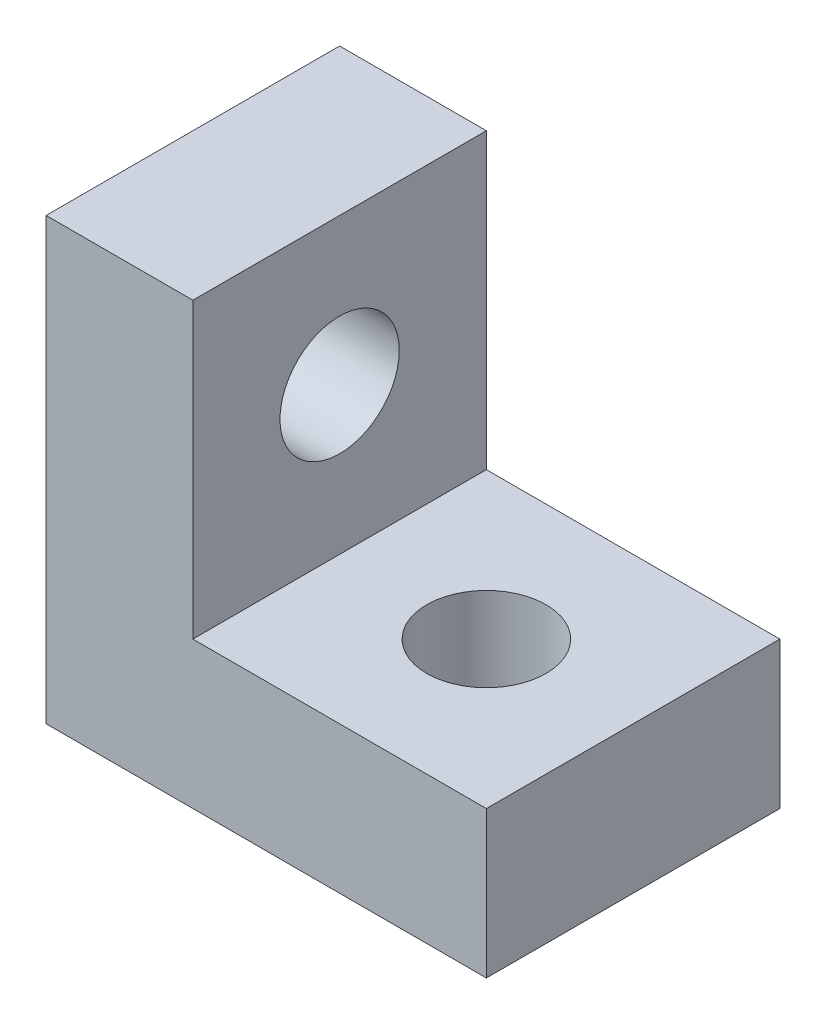
SolidWorks part; units mm, degrees
ref_plane "Front Plane" through (0, 0, 0) normal (0, 0, 1) x (1, 0, 0)
ref_plane "Top Plane" through (0, 0, 0) normal (0, 1, 0) x (1, 0, 0)
ref_plane "Right Plane" through (0, 0, 0) normal (1, 0, 0) x (0, 0, -1)
sketch "Sketch1" plane through (0, 0, 0) normal (0, 0, 1) x (1, 0, 0)
  line L1 (0, 0) -> (11.1626, 0)
  line L2 (0, 0) -> (0, 19.05)
  line L3 (0, 19.05) -> (6.35, 19.05)
  line L4 (6.35, 6.35) -> (6.35, 19.05)
  line L5 (11.1626, 0) -> (19.05, 0)
  line L7 (6.35, 6.35) -> (19.05, 6.35)
  line L8 (19.05, 0) -> (19.05, 6.35)
  dimension "D1" = 12.7
  dimension "D2" = 12.7
  dimension "D3" = 6.35
  dimension "D4" = 6.35
extrude "Boss-Extrude1" add sketch "Sketch1" along normal blind 12.7
sketch "Sketch2" plane through (6.35, 0, 0) normal (1, 0, 0) x (0, 0, -1)
  line L0 (0, 6.35) -> (0, 19.05) construction
  line L1 (-12.7, 19.05) -> (0, 19.05) construction
  point P0 (-6.35, 12.7)
  dimension "D1" = 6.35
  dimension "D2" = 6.35
sketch "Sketch3" plane through (0, 6.35, 0) normal (0, 1, 0) x (1, 0, 0)
  line L0 (19.05, 0) -> (6.35, 0) construction
  line L1 (19.05, -12.7) -> (19.05, 0) construction
  point P0 (12.7, -6.35)
  dimension "D1" = 6.35
  dimension "D2" = 6.35
hole_wizard "13/64 (0.20313) Diameter Hole1" positions "3DSketch1" profile "Sketch4" hole size "13/64" standard "ANSI Inch" end condition through all
sketch3d "3DSketch1"
  point P0 (6.35, 12.7, 6.35)
  point P3 (12.7, 6.35, 6.35)
sketch "Sketch4" plane through (6.35, 12.7, 6.35) normal (0, 1, 0) x (0, 0, -1)
  line L0 (0, 0) -> (0, 6.35)
  line L1 (0, 6.35) -> (2.5798, 6.35)
  line L2 (2.5798, 6.35) -> (2.5798, 0)
  line L5 (2.5798, 0) -> (0, 0)
  line L11 (0, -6.35) -> (0, 107.95) construction
  dimension "Thru Hole Dia." = 5.1595
  dimension "Thru Hole Depth" = 6.35
